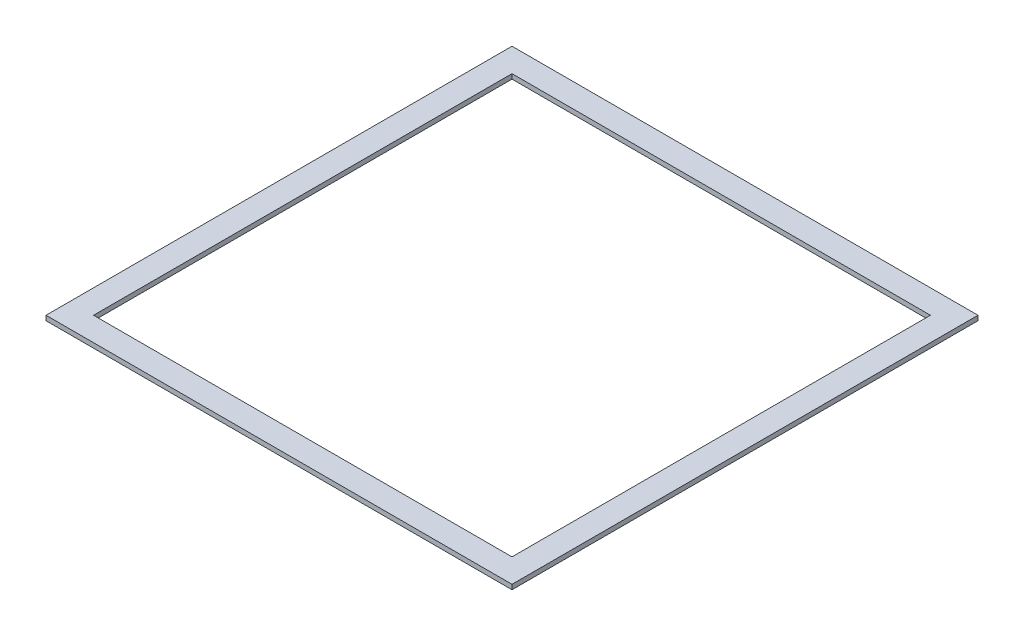
SolidWorks part; units mm, degrees
ref_plane "Alzado" through (0, 0, 0) normal (0, 0, 1) x (1, 0, 0)
ref_plane "Planta" through (0, 0, 0) normal (0, 1, 0) x (1, 0, 0)
ref_plane "Vista lateral" through (0, 0, 0) normal (1, 0, 0) x (0, 0, -1)
sketch "Croquis1" plane through (0, 0, 0) normal (0, 1, 0) x (1, 0, 0)
  line L0 (5, 5) -> (5, 93)
  line L1 (0, 0) -> (98, 0)
  line L2 (0, 0) -> (0, 98)
  line L3 (0, 98) -> (98, 98)
  line L4 (98, 0) -> (98, 98)
  line L5 (5, 93) -> (93, 93)
  line L6 (93, 5) -> (93, 93)
  line L7 (5, 5) -> (93, 5)
  dimension "D1" = 98
  dimension "D2" = 5
extrude "Saliente-Extruir1" add sketch "Croquis1" along normal blind 1
